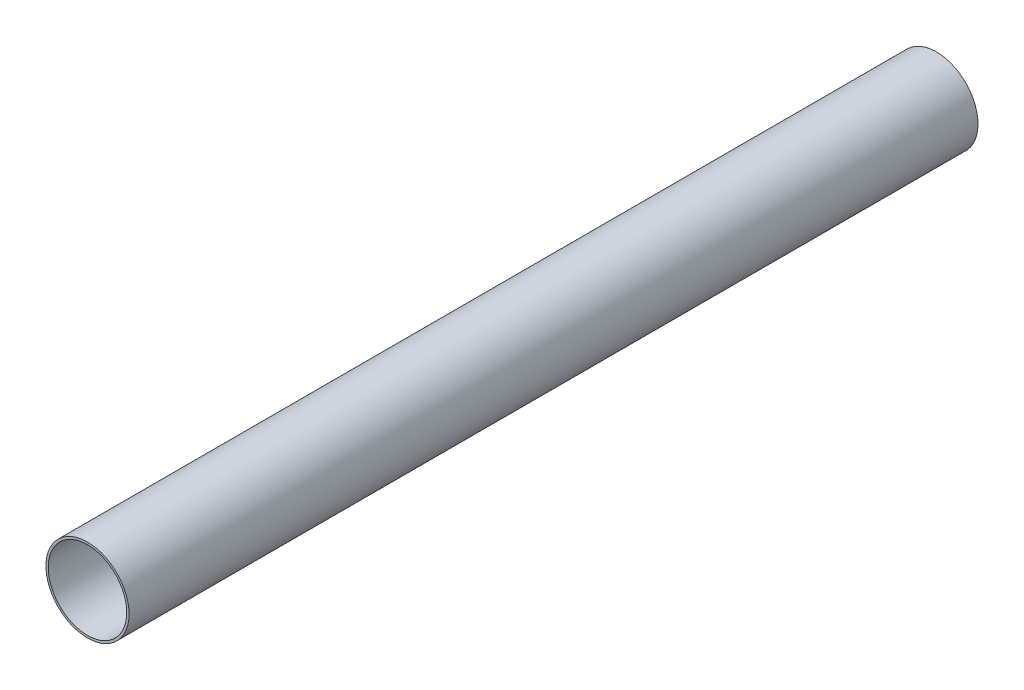
SolidWorks part; units mm, degrees
material "Chrome Stainless Steel"
ref_plane "Front Plane" through (0, 0, 0) normal (0, 0, 1) x (1, 0, 0)
ref_plane "Top Plane" through (0, 0, 0) normal (0, 1, 0) x (1, 0, 0)
ref_plane "Right Plane" through (0, 0, 0) normal (1, 0, 0) x (0, 0, -1)
sketch "Sketch1" plane through (0, 0, 0) normal (0, 0, 1) x (1, 0, 0)
  circle A0 centre (0, 0) radius 12.7
  circle A1 centre (0, 0) radius 12
  dimension "D1" = 25.4
  dimension "D2" = 24
extrude "Boss-Extrude1" add sketch "Sketch1" against normal blind 259.43
equation "\"MinorShaftDiameter\"= 24.0mm"
equation "\"D2@Sketch1\"=\"MinorShaftDiameter\""
